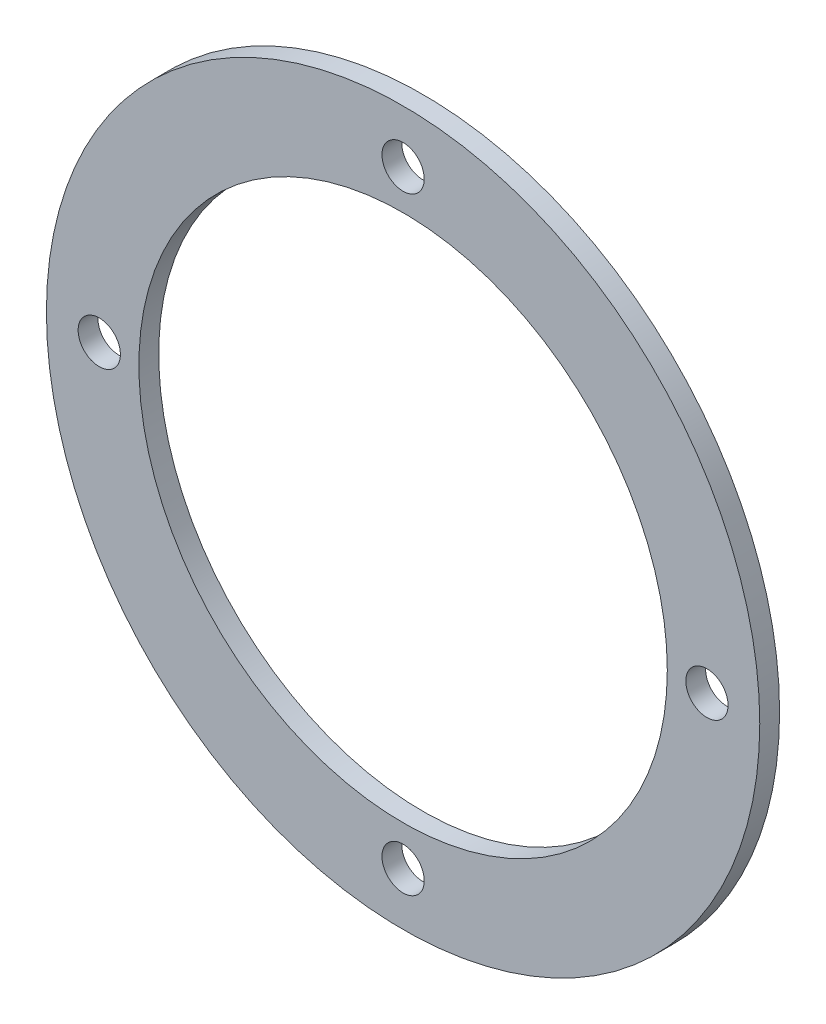
SolidWorks part; units mm, degrees
material "环氧树脂FR-4"
ref_plane "前视基准面" through (0, 0, 0) normal (0, 0, 1) x (1, 0, 0)
ref_plane "上视基准面" through (0, 0, 0) normal (0, 1, 0) x (1, 0, 0)
ref_plane "右视基准面" through (0, 0, 0) normal (1, 0, 0) x (0, 0, -1)
sketch "草图1" plane through (0, 0, 0) normal (0, 0, 1) x (1, 0, 0)
  line L0 (0, 0) -> (0, 23) construction
  circle A0 centre (0, 0) radius 20
  circle A1 centre (0, 0) radius 27
  circle A2 centre (0, 23) radius 1.6
  circle A3 centre (23, 0) radius 1.6
  circle A4 centre (0, 0) radius 20
  circle A5 centre (0, -23) radius 1.6
  circle A6 centre (0, 0) radius 20
  circle A7 centre (-23, 0) radius 1.6
  circle A8 centre (0, 0) radius 20
  dimension "D1" = 40
  dimension "D2" = 54
  dimension "D5" = 3.2
  dimension "D4" = 23
  dimension "D3" = 4
extrude "凸台-拉伸1" add sketch "草图1" along normal blind 1.5
